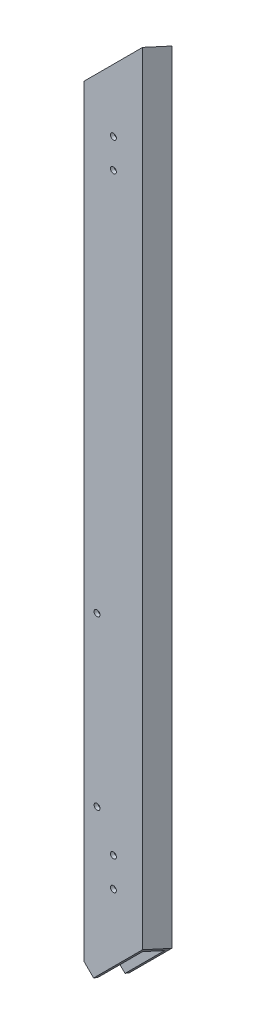
SolidWorks part; units mm, degrees
ref_plane "Front Plane" through (0, 0, 0) normal (0, 0, 1) x (1, 0, 0)
ref_plane "Top Plane" through (0, 0, 0) normal (0, 1, 0) x (1, 0, 0)
ref_plane "Right Plane" through (0, 0, 0) normal (1, 0, 0) x (0, 0, -1)
sketch "Sketch1" plane through (0, 0, 0) normal (0, 1, 0) x (1, 0, 0)
  line L0 (-22.225, 9.525) -> (22.225, 9.525)
  line L1 (-25.4, -12.7) -> (25.4, -12.7)
  line L2 (-25.4, -12.7) -> (-25.4, 12.7)
  line L3 (-25.4, 12.7) -> (25.4, 12.7)
  line L4 (25.4, -12.7) -> (25.4, 12.7)
  line L5 (-25.4, -12.7) -> (25.4, 12.7) construction
  line L6 (-25.4, 12.7) -> (25.4, -12.7) construction
  line L7 (22.225, -9.525) -> (22.225, 9.525)
  line L8 (-22.225, -9.525) -> (22.225, -9.525)
  line L9 (-22.225, -9.525) -> (-22.225, 9.525)
  point P0 (0, 0)
  dimension "D1" = 25.4
  dimension "D2" = 50.8
  dimension "D3" = 3.175
extrude "Boss-Extrude1" add sketch "Sketch1" along normal blind 728.3704
sketch "Sketch2" plane through (0, 0, 12.7) normal (0, 0, 1) x (1, 0, 0)
  line L0 (25.4, 728.3704) -> (-25.4, 677.5704)
  line L1 (-25.4, 728.3704) -> (-25.4, 0) construction
  line L2 (-25.4, 677.5704) -> (-25.4, 728.3704)
  line L3 (-25.4, 728.3704) -> (25.4, 728.3704)
  line L4 (-25.4, 13.9954) -> (-11.4046, 0)
  line L5 (-25.4, 0) -> (25.4, 0) construction
  line L6 (-11.4046, 0) -> (25.4, 36.8046)
  line L7 (25.4, 728.3704) -> (25.4, 0) construction
  line L8 (25.4, 36.8046) -> (25.4, 0)
  line L9 (25.4, 0) -> (-11.4046, 0)
  line L10 (-25.4, 0) -> (-25.4, 13.9954)
  line M6 (-25.4, 0) -> (25.4, 0)
  line M8 (25.4, 728.3704) -> (-25.4, 728.3704)
  line M9 (-25.4, 728.3704) -> (-25.4, 0)
  dimension "D1" = 45
  dimension "D2" = 36.8046
  dimension "D3" = 36.8046
  dimension "D4" = 13.9954
extrude "Cut-Extrude1" cut sketch "Sketch2" against normal through all contours L0 M8 M9 | L4 M9 M6 | L6 L8 L9
ref_plane "Plane1" through (376.8852, 376.8852, 0) normal (0.7071, 0.7071, 0) x (0, 0, -1)
sketch "Sketch3" plane through (376.8852, 376.8852, 0) normal (0.7071, 0.7071, 0) x (0, 0, -1)
  line L0 (-12.7, 497.0751) -> (12.7, 488.8222)
  line L1 (12.7, 497.0751) -> (12.7, 8.0643) construction
  line L2 (12.7, 488.8222) -> (12.7, 497.0751)
  line L3 (12.7, 497.0751) -> (-12.7, 497.0751)
  dimension "D1" = 18
extrude "Cut-Extrude2" cut sketch "Sketch3" against normal through all
sketch "Sketch4" plane through (-5.7023, -5.7023, 0) normal (-0.7071, -0.7071, 0) x (0, 0, 1)
  line L0 (-12.7, 8.0643) -> (12.7, 16.3172)
  line L1 (12.7, 27.8568) -> (12.7, 8.0643) construction
  line L2 (12.7, 16.3172) -> (12.7, 8.0643)
  line L3 (12.7, 8.0643) -> (-12.7, 8.0643)
  dimension "D1" = 18
extrude "Cut-Extrude3" cut sketch "Sketch4" against normal through all
hole_wizard "13/64 (0.20313) Diameter Hole1" positions "Sketch5" profile "Sketch6" hole size "13/64" standard "ANSI Inch"
sketch "Sketch5" plane through (0, 0, -12.7) normal (0, 0, -1) x (-1, 0, 0)
  point P0 (0, 623.0766)
  point P3 (0, 648.4766)
  point P6 (14.2367, 282.194)
  point P9 (14.2367, 136.398)
sketch "Sketch6" plane through (0, 623.0766, -12.7) normal (1, 0, 0) x (0, 1, 0)
  line L0 (0, 0) -> (0, 25.4)
  line L1 (0, 25.4) -> (2.5798, 25.4)
  line L2 (2.5798, 25.4) -> (2.5798, 0)
  line L5 (2.5798, 0) -> (0, 0)
  line L11 (0, -6.35) -> (0, 107.95) construction
  dimension "Thru Hole Dia." = 5.1595
  dimension "Thru Hole Depth" = 25.4
hole_wizard "13/64 (0.20313) Diameter Hole2" positions "Sketch7" profile "Sketch8" hole size "13/64" standard "ANSI Inch"
sketch "Sketch7" plane through (0, 0, 12.7) normal (0, 0, 1) x (1, 0, 0)
  point P0 (0, 106.8944)
  point P3 (0, 81.4944)
sketch "Sketch8" plane through (0, 106.8944, 12.7) normal (1, 0, 0) x (0, -1, 0)
  line L0 (0, 0) -> (0, 25.4)
  line L1 (0, 25.4) -> (2.5798, 25.4)
  line L2 (2.5798, 25.4) -> (2.5798, 0)
  line L5 (2.5798, 0) -> (0, 0)
  line L11 (0, -6.35) -> (0, 107.95) construction
  dimension "Thru Hole Dia." = 5.1595
  dimension "Thru Hole Depth" = 25.4
